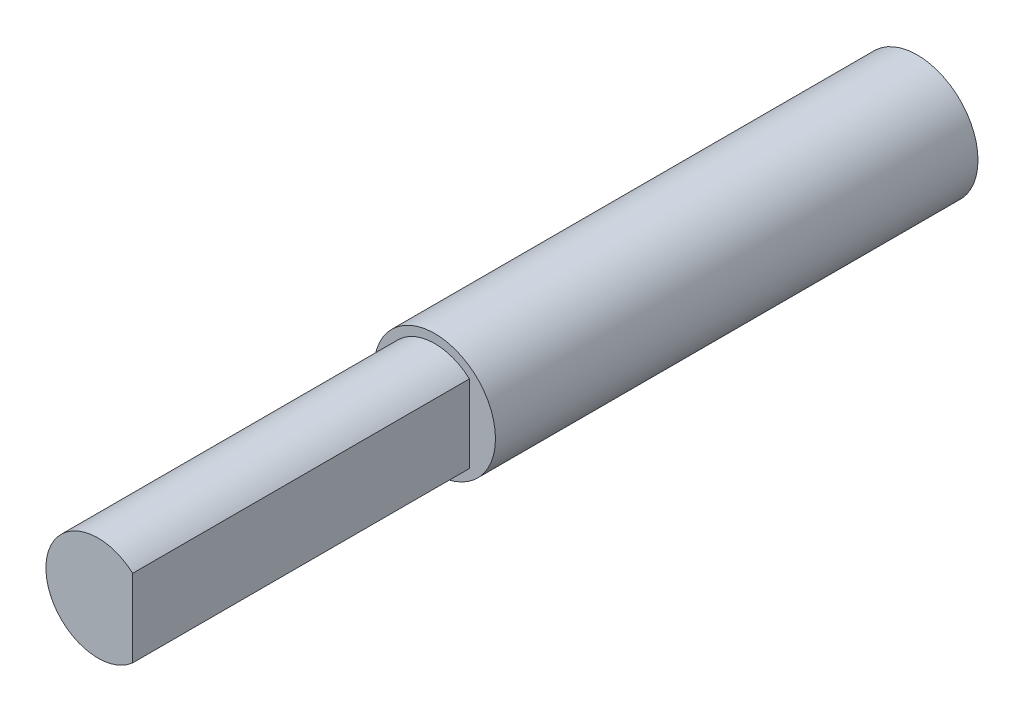
SolidWorks part; units mm, degrees
ref_plane "Front Plane" through (0, 0, 0) normal (0, 0, 1) x (1, 0, 0)
ref_plane "Top Plane" through (0, 0, 0) normal (0, 1, 0) x (1, 0, 0)
ref_plane "Right Plane" through (0, 0, 0) normal (1, 0, 0) x (0, 0, -1)
sketch "Sketch1" plane through (0, 0, 0) normal (0, 0, 1) x (1, 0, 0)
  circle A0 centre (0, 0) radius 1.75
  dimension "D1" = 3.5
extrude "Boss-Extrude1" add sketch "Sketch1" along normal blind 13.9
sketch "Sketch2" plane through (0, 0, 13.9) normal (0, 0, 1) x (1, 0, 0)
  line L0 (1, 1.118) -> (1, -1.118)
  circle A0 centre (0, 0) radius 1.5
  dimension "D1" = 3
  dimension "D2" = 1
extrude "Boss-Extrude2" add sketch "Sketch2" along normal blind 9.7 contours L0 A0
